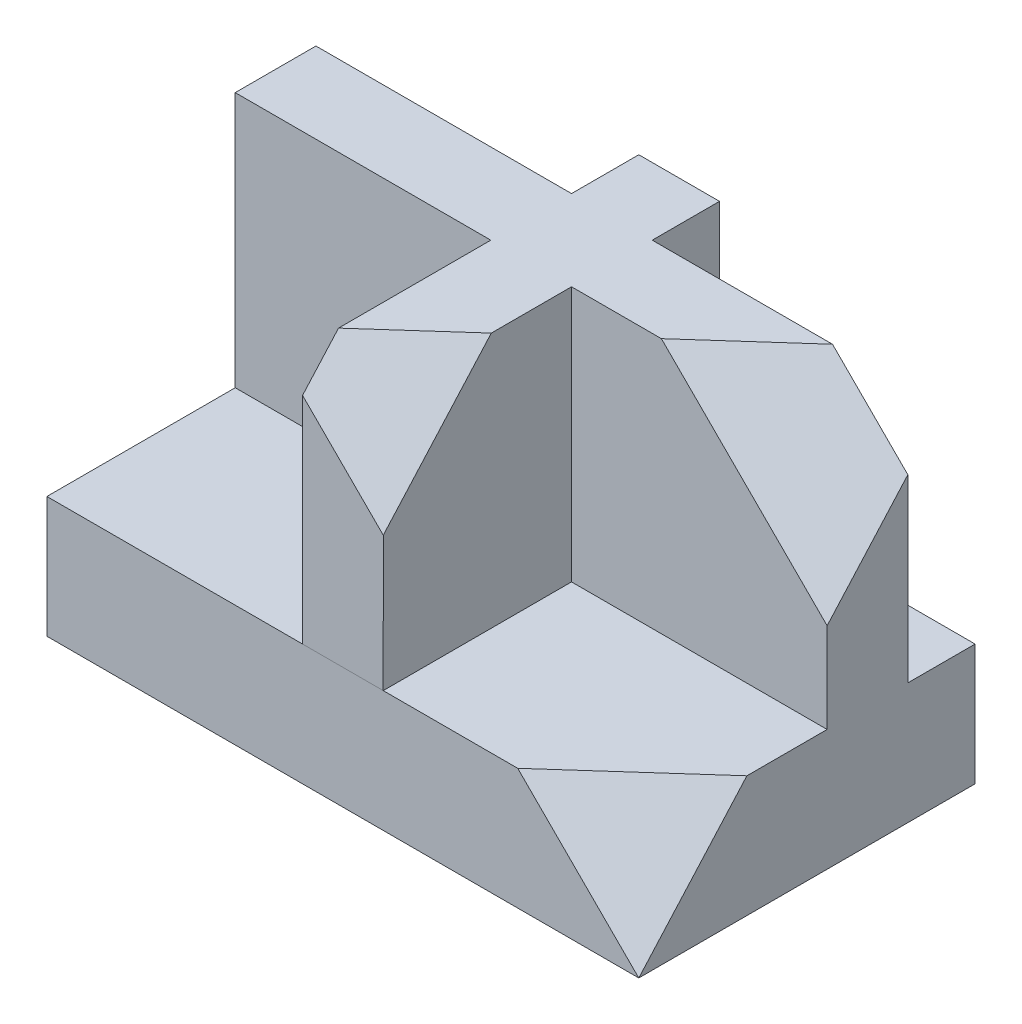
SolidWorks part; units mm, degrees
material "A286 Iron Base Superalloy"
ref_plane "Front Plane" through (0, 0, 0) normal (0, 0, 1) x (1, 0, 0)
ref_plane "Top Plane" through (0, 0, 0) normal (0, 1, 0) x (1, 0, 0)
ref_plane "Right Plane" through (0, 0, 0) normal (1, 0, 0) x (0, 0, -1)
sketch "Sketch1" plane through (0, 0, 0) normal (0, 1, 0) x (1, 0, 0)
  line L1 (-44, 25) -> (44, 25)
  line L2 (-44, 25) -> (-44, -25)
  line L3 (-44, -25) -> (44, -25)
  line L4 (44, 25) -> (44, -25)
  line L5 (-44, 25) -> (44, -25) construction
  line L6 (-44, -25) -> (44, 25) construction
  point P0 (0, 0)
  dimension "D1" = 50
  dimension "D2" = 88
extrude "Boss-Extrude1" add sketch "Sketch1" along normal blind 18
sketch "Sketch2" plane through (0, 18, 0) normal (0, 1, 0) x (1, 0, 0)
  line L0 (-44, 3) -> (-6, 3)
  line L1 (-44, 3) -> (-44, 15)
  line L2 (44, 3) -> (44, 15)
  line L3 (-44, 15) -> (-6, 15)
  line L4 (-44, 25) -> (-44, -25) construction
  line L5 (44, -25) -> (44, 25) construction
  line L6 (-44, -25) -> (44, -25) construction
  line L7 (6, 25) -> (-6, 25)
  line L8 (6, 25) -> (6, 15)
  line L9 (-6, 25) -> (-6, 15)
  line L10 (6, -24.9905) -> (-6, -24.9905)
  line L11 (44, 25) -> (-44, 25) construction
  line L12 (6, 15) -> (44, 15)
  line L13 (6, 3) -> (44, 3)
  line L14 (-6, 3) -> (-6, -24.9905)
  line L15 (6, 3) -> (6, -24.9905)
  dimension "D1" = 12
  dimension "D2" = 28
  dimension "D3" = 12
  dimension "D4" = 38
extrude "Boss-Extrude2" add sketch "Sketch2" along normal blind 38
sketch "Sketch3" plane through (0, 56, 0) normal (0, 1, 0) x (1, 0, 0)
  line L0 (44, 25) -> (6, 25) construction
  line L1 (-44, -25) -> (44, -25) construction
  line L2 (-44, -25) -> (-44, 25) construction
  line L3 (-44, 25) -> (44, 25) construction
  line L4 (44, -25) -> (44, 25) construction
  line L5 (-44, -25) -> (44, 25) construction
  line L6 (-44, 25) -> (44, -25) construction
  point P0 (0, 0)
sketch "Sketch4" plane through (0, 0, 25) normal (0, 0, 1) x (1, 0, 0)
  line L0 (44, 0) -> (-12, 56) construction
  line L1 (-44, 56) -> (44, 56) construction
  line L2 (-44, 0) -> (44, 0) construction
  dimension "D1" = 45
ref_plane "Plane1" through (22.1239, 22.1239, 24.7788) normal (-0.5543, -0.5543, -0.6208) x (-0.8323, 0.3692, 0.4135)
sketch "Sketch5" plane through (22.1239, 22.1239, 24.7788) normal (-0.5543, -0.5543, -0.6208) x (-0.8323, 0.3692, 0.4135)
  line L0 (44.3846, 56.3822) -> (-29.7204, 56.3822)
  line L1 (44.3846, 56.3822) -> (44.3846, -20.1782)
  line L2 (-29.7204, 56.3822) -> (-29.7204, -20.1782)
  line L3 (44.3846, -20.1782) -> (-29.7204, -20.1782)
extrude "Cut-Extrude1" cut sketch "Sketch5" against normal blind 38
